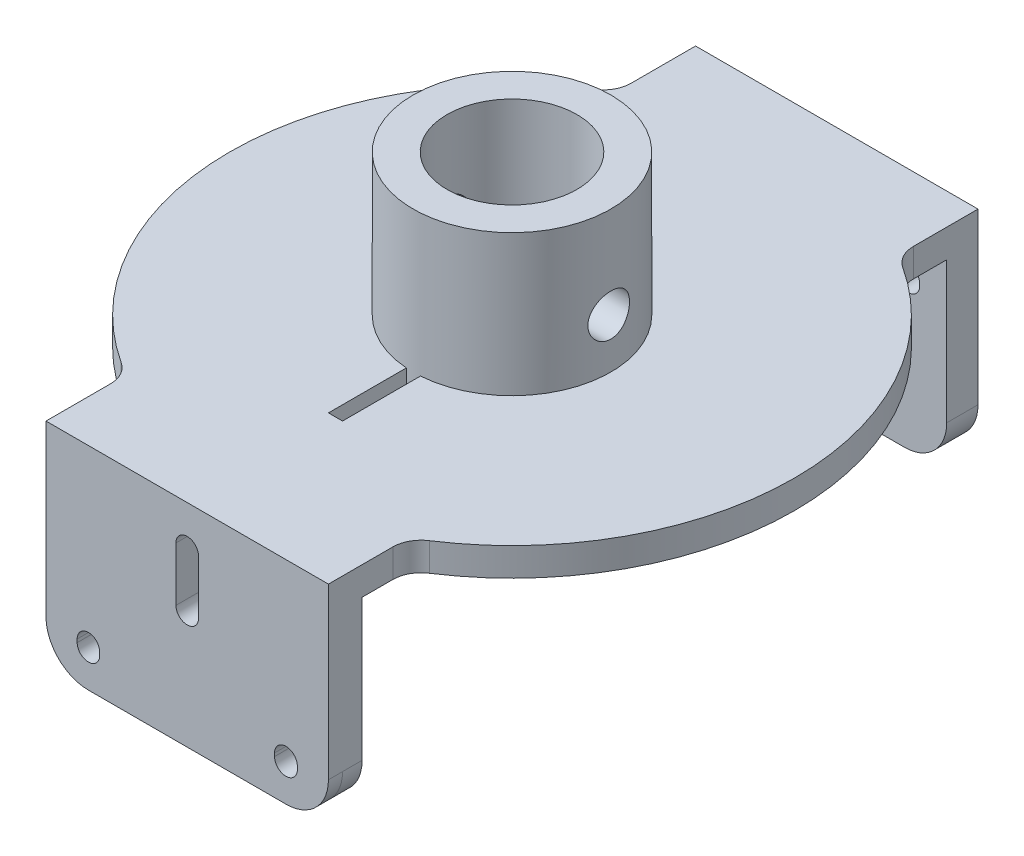
SolidWorks part; units mm, degrees
ref_plane "前视基准面" through (0, 0, 0) normal (0, 0, 1) x (1, 0, 0)
ref_plane "上视基准面" through (0, 0, 0) normal (0, 1, 0) x (1, 0, 0)
ref_plane "右视基准面" through (0, 0, 0) normal (1, 0, 0) x (0, 0, -1)
sketch "草图1" plane through (0, 0, 0) normal (0, 0, 1) x (1, 0, 0)
  line L0 (0, 0) -> (20, 0)
  line L5 (20, 0) -> (20, -13)
  line L6 (20, -13) -> (0, -13)
  line L7 (0, -13) -> (0, 0)
  line L8 (10, 0) -> (10, -2.8) construction
  circle A0 centre (10, -2.8) radius 0.8
  circle A1 centre (17, -9.8) radius 0.8
  circle A2 centre (3, -9.8) radius 0.8
  dimension "D1" = 14
  dimension "D4" = 1.6
  dimension "D5" = 1.6
  dimension "D2" = 20
  dimension "D3" = 7
  dimension "14" = 13
  dimension "D6" = 2.8
extrude "凸台-拉伸1" add sketch "草图1" along normal blind 2
sketch "草图2" plane through (0, 0, 0) normal (0, 1, 0) x (1, 0, 0)
  line L0 (0, 0) -> (0, -44)
  line L2 (20, -44) -> (20, 0)
  line L4 (20, 0) -> (20, 0.5)
  line L5 (20, 0.5) -> (0, 0.5)
  line L6 (0, 0.5) -> (0, 0)
  line L7 (20, -44) -> (20, -44.5)
  line L8 (20, -44.5) -> (0, -44.5)
  line L9 (0, -44.5) -> (0, -44)
extrude "凸台-拉伸2" add sketch "草图2" along normal blind 2
ref_plane "基准面4" through (0, 0, 22) normal (0, 0, 1) x (1, 0, 0)
mirror "镜向1" about plane through (0, 0, 22) normal (0, 0, 1) of "凸台-拉伸1"
sketch "草图3" plane through (0, 2, 0) normal (0, 1, 0) x (1, 0, 0)
  circle A0 centre (10, -22) radius 4.6
  circle A1 centre (10, -22) radius 7
extrude "凸台-拉伸3" add sketch "草图3" along normal blind 10
sketch "草图4" plane through (0, 2, 0) normal (0, 1, 0) x (1, 0, 0)
  circle A0 centre (10, -22) radius 20
extrude "凸台-拉伸4" add sketch "草图4" against normal blind 2 contours A0
ref_plane "基准面5" through (0, 5.5, 0) normal (0, 1, 0) x (1, 0, 0)
sketch "草图6" plane through (0, 5.5, 0) normal (0, 1, 0) x (1, 0, 0)
  line L0 (22.9766, -21.9965) -> (-13.4577, -21.9965) construction
  line L1 (0.1212, -21.9965) -> (0.1212, -20.5215)
  line L8 (0.1212, -20.5215) -> (20.2988, -20.5215)
  line L9 (20.2988, -20.5215) -> (20.2988, -21.9965)
  line L11 (0.1212, -21.9965) -> (20.2988, -21.9965)
revolve "切除-旋转1" cut sketch "草图6" angle 360 about L0
ref_plane "基准面6" through (0, 0, 34.5) normal (0, 0, 1) x (1, 0, 0)
sketch "草图7" plane through (0, 0, 34.5) normal (0, 0, 1) x (1, 0, 0)
  line L0 (10, 12) -> (10, -1.5594) construction
  line L2 (14.6, 12) -> (5.4, 12) construction
  line L3 (10, 12) -> (10, 2) construction
  line L4 (10, -0.1746) -> (10.5, -0.1746)
  line L5 (10.5, -0.1746) -> (10.5, 2.6134)
  line L6 (10.5, 2.6134) -> (9.5, 2.6134)
  line L7 (9.5, 2.6134) -> (9.5, -0.1746)
  line L8 (9.5, -0.1746) -> (10, -0.1746)
fillet "圆角1" radius 3 4 edges at (0, -13, 43) (20, -13, 43) (20, -13, 1) (0, -13, 1)
extrude "切除-拉伸1" cut sketch "草图7" against normal up to surface (5.5179 mm away)
sketch "草图8" plane through (0, 0, 0) normal (0, 0, -1) x (-1, 0, 0)
  line L1 (0, 0) -> (0, -13)
  line L2 (0, -13) -> (-20, -13)
  line L3 (-20, -13) -> (-20, 0)
  line L4 (-10, 2) -> (-10, 3.4475) construction
  line L5 (-20, 0) -> (-20, 2)
  line L6 (-20, 2) -> (0, 2) construction
  line L7 (-20, 2) -> (-20, 0) construction
  line L8 (-20, 2) -> (0, 2)
  line L9 (0, 2) -> (0, 0)
  line L10 (-17.25, -11.4195) -> (-17.25, -9.6925) construction
  line L11 (-18.05, -11.4195) -> (-18.05, -9.6925)
  line L12 (-16.45, -11.4195) -> (-16.45, -9.6925)
  line L13 (-2.75, -11.4195) -> (-2.75, -9.6925) construction
  line L14 (-1.95, -11.4195) -> (-1.95, -9.6925)
  line L15 (-3.55, -11.4195) -> (-3.55, -9.6925)
  arc A5 (-18.05, -11.4195) -> (-16.45, -11.4195) centre (-17.25, -11.4195) ccw
  arc A6 (-16.45, -9.6925) -> (-18.05, -9.6925) centre (-17.25, -9.6925) ccw
  arc A8 (-1.95, -11.4195) -> (-3.55, -11.4195) centre (-2.75, -11.4195) cw
  arc A9 (-3.55, -9.6925) -> (-1.95, -9.6925) centre (-2.75, -9.6925) cw
  point P19 (-17.25, -10.556)
  point P24 (-2.75, -10.556)
  dimension "D2" = 20
  dimension "D4" = 13
extrude "凸台-拉伸5" add sketch "草图8" along normal blind 2
sketch "草图9" plane through (0, 0, 44) normal (0, 0, 1) x (1, 0, 0)
  line L1 (20, 0) -> (20, -13)
  line L2 (20, -13) -> (0, -13)
  line L3 (0, -13) -> (0, 0)
  line L4 (10, 0) -> (10, -2.8) construction
  line L5 (0, 0) -> (0, 2)
  line L6 (0, 2) -> (20, 2)
  line L7 (20, 2) -> (20, 0)
  circle A0 centre (10, -2.8) radius 0.8
  dimension "D5" = 1.6
  dimension "D2" = 20
  dimension "D4" = 13
extrude "凸台-拉伸6" add sketch "草图9" along normal blind 2
sketch "草图10" plane through (0, 0, 0) normal (0, -1, 0) x (1, 0, 0)
  line L0 (0, 42) -> (0, 42.6138)
  line L1 (0, 42) -> (3, 42) construction
  line L2 (20, 42) -> (0, 42) construction
  line L3 (0, 42.6138) -> (20, 42.6138)
  line L4 (20, 44) -> (20, 42) construction
  line L5 (20, 42.6138) -> (20, 1.2138)
  line L6 (20, 2) -> (20, 0) construction
  line L7 (20, 1.2138) -> (0, 1.2138)
  line L8 (0, 0) -> (0, 2) construction
  line L9 (0, 1.2138) -> (0, 42.6138)
  line L10 (20, 21.9138) -> (34.3654, 21.9138) construction
  line M2 (20, 2) -> (20, 4.6795)
  line M4 (20, 39.3205) -> (20, 42)
  line M5 (20, 42) -> (0, 42)
  line M6 (0, 42) -> (0, 39.3205)
  line M8 (0, 4.6795) -> (0, 2)
  line M9 (0, 2) -> (20, 2)
  line M10 (9.5, 34.5) -> (10.5, 34.5)
  line M11 (10.5, 34.5) -> (10.5, 28.9821)
  arc M12 (10.5, 28.9821) -> (9.5, 28.9821) centre (10, 22) ccw
  line M13 (9.5, 28.9821) -> (9.5, 34.5)
  dimension "D1" = 20.7
extrude "切除-拉伸2" cut sketch "草图10" along normal up to surface (13 mm away) contours L9 L5 M8 M9 M2 M4 M5 M6 M13 M10 M11 M12 | L5 L3 L0 M5 | L9 L7 L5 M9 up to face at (10, -13, 0)
fillet "圆角2" radius 3 12 edges at (20, -11.5, 0) (0, -13, -1) (0, -11.5, 0) (18.5, -13, 0) (1.5, -13, 0) (20, -13, -1) (0, -11.5, 44) (1.5, -13, 44) (18.5, -13, 44) (0, -13, 45) (20, -13, 45) (20, -11.5, 44)
ref_plane "基准面7" through (0, 0, -2) normal (0, 0, -1) x (-1, 0, 0)
sketch "草图11" plane through (0, 0, -2) normal (0, 0, -1) x (-1, 0, 0)
  line L0 (-10, 2) -> (-10, 3.4475) construction
  line L1 (-20, 2) -> (0, 2)
  line L2 (-17.25, -2.8635) -> (-17.25, -1.1365) construction
  line L3 (-18.05, -2.8635) -> (-18.05, -1.1365)
  line L4 (-16.45, -2.8635) -> (-16.45, -1.1365)
  line L5 (-2.75, -2.8635) -> (-2.75, -1.1365) construction
  line L6 (-1.95, -2.8635) -> (-1.95, -1.1365)
  line L7 (-3.55, -2.8635) -> (-3.55, -1.1365)
  line L8 (-3, 2) -> (-17, 2) construction
  line L9 (-20, 0) -> (0, 0) construction
  line L10 (-20, 2) -> (-20, 0) construction
  line L11 (-20, 2) -> (-20, -10) construction
  arc A0 (-18.05, -2.8635) -> (-16.45, -2.8635) centre (-17.25, -2.8635) ccw
  arc A1 (-16.45, -1.1365) -> (-18.05, -1.1365) centre (-17.25, -1.1365) ccw
  arc A2 (-1.95, -2.8635) -> (-3.55, -2.8635) centre (-2.75, -2.8635) cw
  arc A3 (-3.55, -1.1365) -> (-1.95, -1.1365) centre (-2.75, -1.1365) cw
  point P8 (-17.25, -2)
  point P13 (-2.75, -2)
  point P18 (-10, 2)
  arc M1 (-16.45, -11.4195) -> (-18.05, -11.4195) centre (-17.25, -11.4195) cw
  line M2 (-18.05, -11.4195) -> (-18.05, -9.6925)
  arc M3 (-18.05, -9.6925) -> (-16.45, -9.6925) centre (-17.25, -9.6925) cw
  line M4 (-16.45, -9.6925) -> (-16.45, -11.4195)
  arc M11 (-1.95, -11.4195) -> (-3.55, -11.4195) centre (-2.75, -11.4195) cw
  line M12 (-3.55, -11.4195) -> (-3.55, -9.6925)
  arc M13 (-3.55, -9.6925) -> (-1.95, -9.6925) centre (-2.75, -9.6925) cw
  line M14 (-1.95, -9.6925) -> (-1.95, -11.4195)
  dimension "D1" = 2
extrude "切除-拉伸3" cut sketch "草图11" against normal blind 10 contours M1 M4 M3 M2 | M11 M14 M13 M12
sketch "草图12" plane through (0, 0, 46) normal (0, 0, 1) x (1, 0, 0)
  line L0 (10, -0.878) -> (10, -4.7038) construction
  line L1 (10.8, -0.878) -> (10.8, -4.7038)
  line L2 (9.2, -0.878) -> (9.2, -4.7038)
  line L3 (3.0041, -10.2606) -> (3.0041, -10.4839) construction
  line L4 (3.8, -10.2606) -> (3.8, -10.4839)
  line L5 (2.2083, -10.2606) -> (2.2083, -10.4839)
  line L6 (16.9925, -10.2606) -> (16.9925, -10.4839) construction
  line L7 (17.8, -10.2606) -> (17.8, -10.4839)
  line L8 (16.185, -10.2606) -> (16.185, -10.4839)
  arc A2 (10.8, -0.878) -> (9.2, -0.878) centre (10, -0.878) ccw
  arc A3 (9.2, -4.7038) -> (10.8, -4.7038) centre (10, -4.7038) ccw
  arc A5 (3.8, -10.2606) -> (2.2083, -10.2606) centre (3.0041, -10.2606) ccw
  arc A6 (2.2083, -10.4839) -> (3.8, -10.4839) centre (3.0041, -10.4839) ccw
  arc A8 (17.8, -10.2606) -> (16.185, -10.2606) centre (16.9925, -10.2606) ccw
  arc A9 (16.185, -10.4839) -> (17.8, -10.4839) centre (16.9925, -10.4839) ccw
  point P2 (17, -11.5059)
  point P3 (17, -10.8373)
  point P4 (17, -11.2839)
  point P5 (3, -10.8373)
  point P7 (10, -2.7909)
  point P12 (3.0041, -10.3723)
  point P15 (3, -11.2839)
  point P16 (3.0041, -10.2606)
  point P22 (16.9925, -10.3723)
  point P25 (16.9925, -10.2606)
extrude "切除-拉伸4" cut sketch "草图12" against normal blind 10
fillet "圆角3" radius 2 3 edges at (20, 1, 4.6795) (0, 1, 4.6795) (0, 1, 39.3205)
sketch "草图13" plane through (0, 0, -2) normal (0, 0, -1) x (-1, 0, 0)
  line L0 (-10, 2) -> (-10, 3.4475) construction
  line L1 (-20, 2) -> (0, 2)
  line L2 (-17.25, -2.8635) -> (-17.25, -1.1365) construction
  line L3 (-18.05, -2.8635) -> (-18.05, -1.1365)
  line L4 (-16.45, -2.8635) -> (-16.45, -1.1365)
  line L5 (-2.75, -2.8635) -> (-2.75, -1.1365) construction
  line L6 (-1.95, -2.8635) -> (-1.95, -1.1365)
  line L7 (-3.55, -2.8635) -> (-3.55, -1.1365)
  line L8 (0, 2) -> (-20, 2) construction
  line L9 (-20, 2) -> (-20, -13)
  line L10 (-20, -13) -> (0, -13)
  line L11 (0, -13) -> (0, 2)
  line L12 (-20, 0) -> (0, 0) construction
  arc A0 (-18.05, -2.8635) -> (-16.45, -2.8635) centre (-17.25, -2.8635) ccw
  arc A1 (-16.45, -1.1365) -> (-18.05, -1.1365) centre (-17.25, -1.1365) ccw
  arc A2 (-1.95, -2.8635) -> (-3.55, -2.8635) centre (-2.75, -2.8635) cw
  arc A3 (-3.55, -1.1365) -> (-1.95, -1.1365) centre (-2.75, -1.1365) cw
  point P8 (-17.25, -2)
  point P13 (-2.75, -2)
  point P18 (-10, 2)
  dimension "D1" = 2
extrude "凸台-拉伸7" add sketch "草图13" against normal up to surface (3.2138 mm away) up to face at (2.8783, -10.4516, 1.2138)
fillet "圆角4" radius 3 2 edges at (0, -13, -0.3931) (20, -13, -0.3931)
sketch "草图14" plane through (0, 0, -2) normal (0, 0, -1) x (-1, 0, 0)
  line L0 (-10, 2) -> (-10, 3.4475) construction
  line L1 (-20, 2) -> (0, 2)
  line L2 (-17.2839, -2.5739) -> (-17.2839, -2.421) construction
  line L3 (-18.0839, -2.5739) -> (-18.0839, -2.421)
  line L4 (-16.4839, -2.5739) -> (-16.4839, -2.421)
  line L5 (-2.7161, -2.5739) -> (-2.7161, -2.421) construction
  line L6 (-1.9161, -2.5739) -> (-1.9161, -2.421)
  line L7 (-3.5161, -2.5739) -> (-3.5161, -2.421)
  line L8 (-20, 2) -> (-20, -13)
  line L9 (-20, -13) -> (0, -13)
  line L10 (0, -13) -> (0, 2)
  line L11 (-20, -0.4975) -> (0, -0.4975) construction
  arc A0 (-18.0839, -2.5739) -> (-16.4839, -2.5739) centre (-17.2839, -2.5739) ccw
  arc A1 (-16.4839, -2.421) -> (-18.0839, -2.421) centre (-17.2839, -2.421) ccw
  arc A2 (-1.9161, -2.5739) -> (-3.5161, -2.5739) centre (-2.7161, -2.5739) cw
  arc A3 (-3.5161, -2.421) -> (-1.9161, -2.421) centre (-2.7161, -2.421) cw
  point P8 (-17.2839, -2.4975)
  point P13 (-2.7161, -2.4975)
  point P18 (-10, 2)
  point P23 (0, 0)
  point P24 (-17.2839, -2.5739)
  point P25 (0, 0)
  point P26 (0, 0)
  point P27 (-17.2839, -3.471)
  point P28 (0, 0)
  point P29 (-17.2839, -3.471)
  point P30 (-17.2839, -2.7238)
  point P31 (0, 0)
  point P32 (-17.2839, -2.5739)
  dimension "D1" = 2
extrude "切除-拉伸5" cut sketch "草图14" against normal up to surface (3.2138 mm away) contours L4 A1 L3 A0 | A3 L7 A2 L6 | L9 L10 L1 L8
sketch "草图15" plane through (0, 0, 0) normal (0, -1, 0) x (1, 0, 0)
  line L0 (10.5, 31.7411) -> (10.5, 31.2411)
  line L1 (10.5, 28.9821) -> (10.5, 34.5) construction
  line L2 (10.5, 31.2411) -> (14.5, 31.2411)
  line L3 (14.5, 31.2411) -> (14.5, 32.2411)
  line L4 (14.5, 32.2411) -> (10.5, 32.2411)
  line L5 (10.5, 32.2411) -> (10.5, 31.2411)
  line M15 (10.5, 34.5) -> (10.5, 28.9821)
extrude "切除-拉伸6" cut sketch "草图15" against normal blind 1 contours L3 L4 L2 M15
sketch "草图16" plane through (0, 2, 0) normal (0, 1, 0) x (1, 0, 0)
  line L0 (0, 2) -> (20, 2)
  line L1 (20, 2) -> (20, 1)
  line L2 (20, -3.5609) -> (20, 2) construction
  line L3 (20, 1) -> (0, 1)
  line L4 (0, 2) -> (0, -3.5609) construction
  line L5 (0, 1) -> (0, 2)
  line L6 (10, -22) -> (35.2183, -22) construction
  line L7 (0, -45) -> (0, -46)
  line L8 (20, -45) -> (0, -45)
  line L9 (20, -46) -> (20, -45)
  line L10 (0, -46) -> (20, -46)
extrude "切除-拉伸7" cut sketch "草图16" against normal up to surface (15 mm away) up to face at (10, -13, -0.3931)
